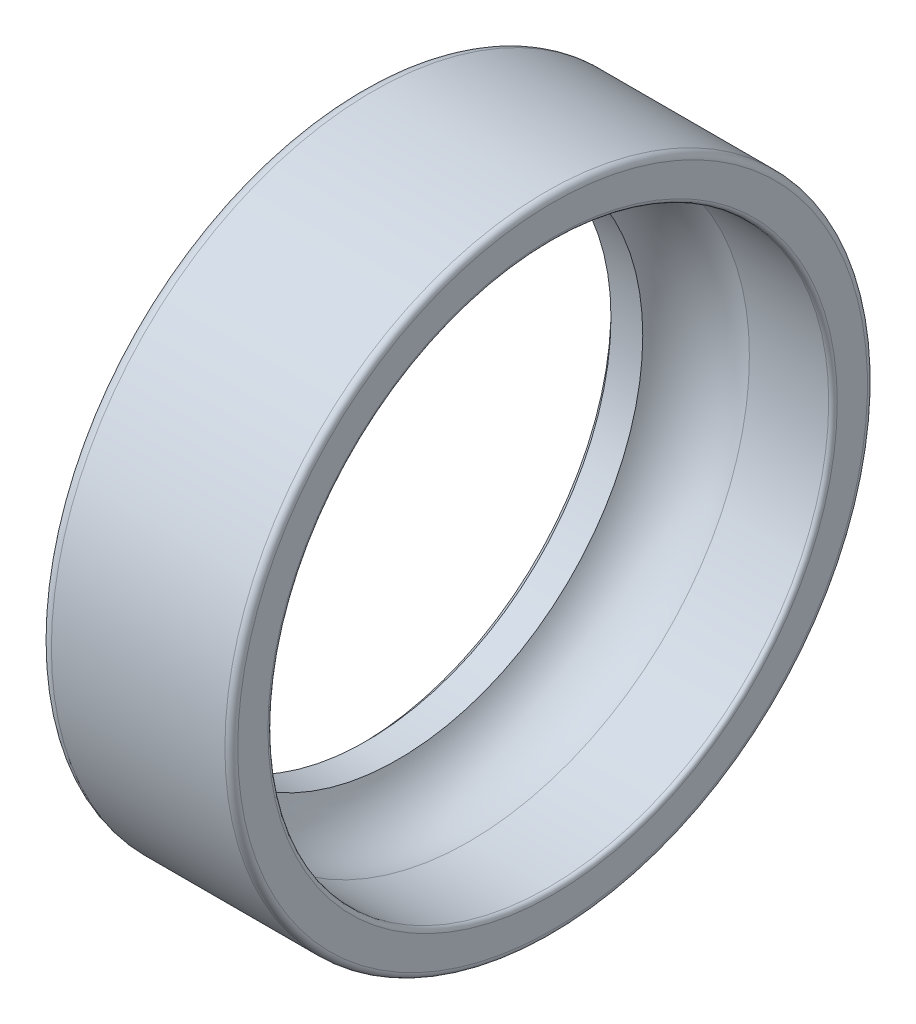
SolidWorks part; units mm, degrees
ref_plane "Front Plane" through (0, 0, 0) normal (0, 0, 1) x (1, 0, 0)
ref_plane "Top Plane" through (0, 0, 0) normal (0, 1, 0) x (1, 0, 0)
ref_plane "Right Plane" through (0, 0, 0) normal (1, 0, 0) x (0, 0, -1)
ref_plane "Plane1" through (0, 0, 0) normal (0, 0, 1) x (1, 0, 0)
sketch "Sketch1" plane through (0, 0, 0) normal (0, 0, 1) x (1, 0, 0)
  line L0 (0, 11.725) -> (0.3, 11.425)
  line L1 (0.3, 11.425) -> (1.7844, 11.425)
  line L2 (5.097, 13.09) -> (8.8, 13.09)
  line L3 (9, 13.29) -> (9, 14.7)
  line L4 (8.7, 15) -> (0.6, 15)
  line L5 (0, 14.4) -> (0, 11.725)
  line L6 (9, 0) -> (0, 0) construction
  arc A0 (1.7844, 11.425) -> (5.097, 13.09) centre (4.5, 10.15) cw
  arc A1 (8.8, 13.09) -> (9, 13.29) centre (8.8, 13.29) ccw
  arc A2 (9, 14.7) -> (8.7, 15) centre (8.7, 14.7) ccw
  arc A3 (0.6, 15) -> (0, 14.4) centre (0.6, 14.4) ccw
revolve "Revolve1" add sketch "Sketch1" angle 360 about L6
